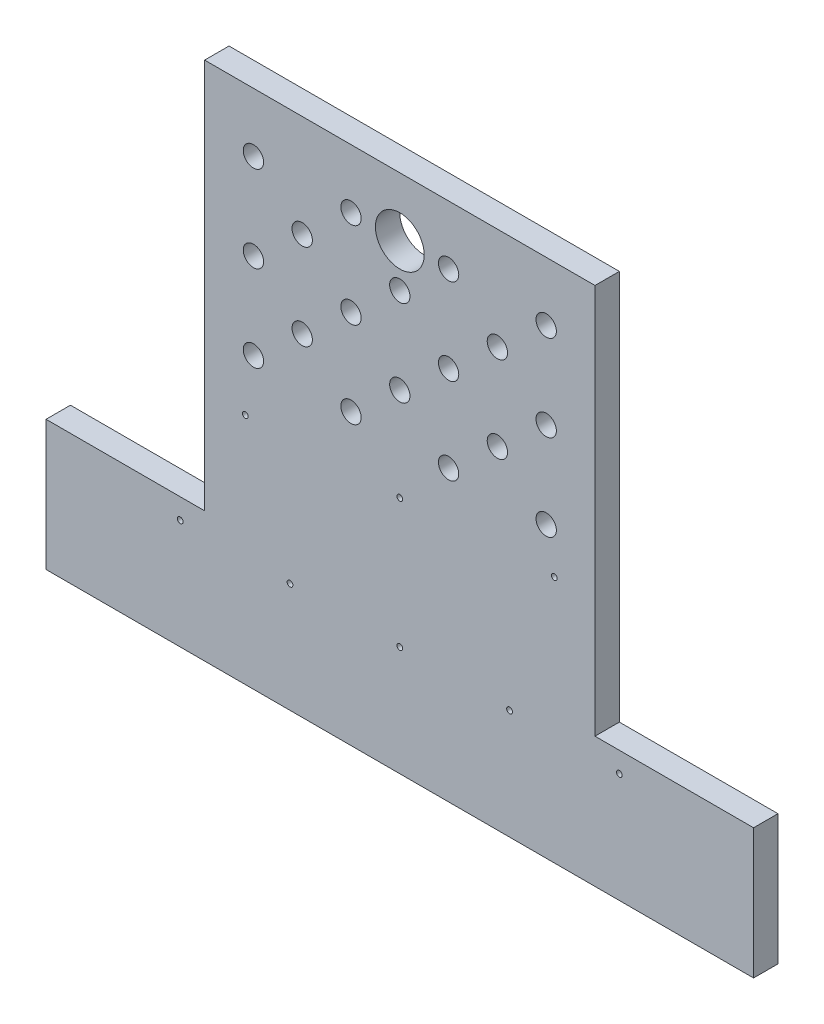
SolidWorks part; units mm, degrees
material "Pine"
ref_plane "Front Plane" through (0, 0, 0) normal (0, 0, 1) x (1, 0, 0)
ref_plane "Top Plane" through (0, 0, 0) normal (0, 1, 0) x (1, 0, 0)
ref_plane "Right Plane" through (0, 0, 0) normal (1, 0, 0) x (0, 0, -1)
sketch "Sketch1" plane through (0, 0, 0) normal (0, 0, 1) x (1, 0, 0)
  line L0 (-152.4, 50.8) -> (-152.4, 355.6)
  line L1 (-276.225, -50.8) -> (276.225, -50.8)
  line L2 (-276.225, -50.8) -> (-276.225, 50.8)
  line L3 (-276.225, 50.8) -> (276.225, 50.8) construction
  line L4 (276.225, -50.8) -> (276.225, 50.8)
  line L5 (-276.225, -50.8) -> (276.225, 50.8) construction
  line L6 (-276.225, 50.8) -> (276.225, -50.8) construction
  line L7 (-152.4, 355.6) -> (152.4, 355.6)
  line L8 (152.4, 355.6) -> (152.4, 50.8)
  line L9 (0, 0) -> (0, 355.6) construction
  line L10 (-152.4, 50.8) -> (-276.225, 50.8)
  line L11 (152.4, 50.8) -> (276.225, 50.8)
  point P0 (0, 0)
  dimension "D1" = 552.45
  dimension "D2" = 101.6
  dimension "D3" = 304.8
  dimension "D4" = 304.8
extrude "Boss-Extrude1" add sketch "Sketch1" along normal blind 19.05
sketch "Sketch2" plane through (0, 0, 19.05) normal (0, 0, 1) x (1, 0, 0)
  line L0 (-76.2, 355.6) -> (-76.2, -50.8) construction
  line L1 (152.4, 355.6) -> (-152.4, 355.6) construction
  line L2 (-276.225, -50.8) -> (276.225, -50.8) construction
  line L3 (0, 355.6) -> (0, -50.8) construction
  line L4 (76.2, 355.6) -> (76.2, -50.8) construction
  line L5 (152.4, 355.6) -> (152.4, -50.8) construction
  line L6 (-152.4, 355.6) -> (-152.4, -50.8) construction
  line L7 (-114.3, 355.6) -> (-114.3, -50.8) construction
  line L8 (-38.1, -50.8) -> (-38.1, 355.6) construction
  line L9 (38.1, 355.6) -> (38.1, -50.8) construction
  line L10 (114.3, -50.8) -> (114.3, 355.6) construction
  line L11 (-114.3, 309.5625) -> (-114.3, 242.2525) construction
  line L12 (-114.3, 242.2525) -> (-114.3, 174.9425) construction
  circle A0 centre (-114.3, 309.5625) radius 7.9375
  circle A1 centre (-38.1, 309.5625) radius 7.9375
  circle A2 centre (38.1, 309.5625) radius 7.9375
  circle A3 centre (114.3, 309.5625) radius 7.9375
  circle A4 centre (-76.2, 275.9075) radius 7.9375
  circle A5 centre (0, 275.9075) radius 7.9375
  circle A6 centre (76.2, 275.9075) radius 7.9375
  circle A8 centre (-114.3, 242.2525) radius 7.9375
  circle A9 centre (-38.1, 242.2525) radius 7.9375
  circle A10 centre (38.1, 242.2525) radius 7.9375
  circle A11 centre (114.3, 242.2525) radius 7.9375
  circle A12 centre (76.2, 208.5975) radius 7.9375
  circle A13 centre (0, 208.5975) radius 7.9375
  circle A14 centre (-76.2, 208.5975) radius 7.9375
  circle A15 centre (-114.3, 174.9425) radius 7.9375
  circle A16 centre (-38.1, 174.9425) radius 7.9375
  circle A17 centre (38.1, 174.9425) radius 7.9375
  circle A18 centre (114.3, 174.9425) radius 7.9375
  point P36 (-76.2, 283.845)
  point P39 (-114.3, 301.625)
  point P42 (-114.3, 317.5)
  point P43 (-114.3, 250.19)
  point P44 (-76.2, 267.97)
  point P61 (-114.3, 182.88)
  point P69 (-76.2, 200.66)
  dimension "D1" = 15.875
  dimension "D2" = 17.78
  dimension "D6" = 17.78
  dimension "D8" = 17.78
  dimension "D3" = 38.1
  dimension "D5" = 2
  dimension "D7" = 2
extrude "Cut-Extrude1" cut sketch "Sketch2" against normal through all
sketch "Sketch5" plane through (0, 0, 0) normal (0, 0, -1) x (-1, 0, 0)
  line L0 (-85.725, 34.925) -> (-171.45, 34.925) construction
  line L2 (-85.725, 34.925) -> (0, 34.925) construction
  line L3 (0, 34.925) -> (85.725, 34.925) construction
  line L4 (85.725, 34.925) -> (171.45, 34.925) construction
  line L5 (171.45, 34.925) -> (257.175, 34.925) construction
  line L6 (257.175, 50.8) -> (257.175, 19.05) construction
  line L7 (-171.45, 34.925) -> (-257.175, 34.925) construction
  line L8 (-257.175, 50.8) -> (-257.175, 19.05) construction
hole_wizard "CSK for #8 Flat Head Machine Screw1" positions "Sketch6" profile "Sketch7" countersink size "#8" standard "ANSI Inch" end condition through all
sketch "Sketch6" plane through (0, 0, 0) normal (0, 0, -1) x (-1, 0, 0)
  point P1 (-171.45, 34.925)
  point P4 (-85.725, 34.925)
  point P7 (0, 34.925)
  point P10 (171.45, 34.925)
  point P13 (85.725, 34.925)
  point P16 (-120.65, 142.5793)
  point P18 (0, 135.7913)
  point P20 (120.65, 131.4668)
sketch "Sketch7" plane through (171.45, 34.925, 0) normal (1, 0, 0) x (0, 1, 0)
  line L0 (0, 0) -> (0, 19.05)
  line L1 (0, 19.05) -> (2.2479, 19.05)
  line L2 (2.2479, 19.05) -> (2.2479, 2.2645)
  line L3 (2.2479, 2.2645) -> (4.2164, 0)
  line L5 (4.2164, 0) -> (0, 0)
  line L6 (-2.2479, 2.2645) -> (-4.2164, 0) construction
  line L11 (0, -6.35) -> (0, 107.95) construction
  dimension "Thru Hole Dia." = 4.4958
  dimension "Thru Hole Depth" = 19.05
  dimension "Near C'Sink Dia." = 8.4328
  dimension "Near C'Sink Angle" = 82
hole_wizard "Hole1" positions "Sketch9" profile "Sketch10" legacy end condition through all
sketch "Sketch9" plane through (0, 0, 19.05) normal (0, 0, 1) x (1, 0, 0)
  line L0 (-38.1, 309.5625) -> (38.1, 309.5625) construction
  point P0 (0, 309.5625)
sketch "Sketch10" plane through (0, 309.5625, 19.05) normal (1, 0, 0) x (0, -1, 0)
  line L0 (0, 0) -> (0, 19.05)
  line L1 (0, 19.05) -> (19.05, 19.05)
  line L2 (19.05, 19.05) -> (19.05, 0)
  line L3 (19.05, 0) -> (0, 0)
  line L4 (0, 110) -> (0, -10) construction
  dimension "Diameter" = 38.1
  dimension "Depth" = 19.05
sketch "Sketch13" plane through (0, 0, 0) normal (0, 0, -1) x (-1, 0, 0)
  line B0 (-276.225, -50.8) -> (276.225, -50.8)
  line B1 (30.2754, 281.3107) -> (30.2765, 290.0355)
  line B2 (30.2746, 258.2859) -> (30.2746, 267.0107)
  arc B3 (19.7008, 287.3363) -> (22.3391, 289.9991) centre (19.7009, 289.9746) ccw
  arc B4 (22.3372, 258.3232) -> (19.6992, 260.9863) centre (19.6991, 258.348) ccw
  arc B5 (-26.9928, 286.1302) -> (-24.5316, 286.489) centre (-26.3058, 290.0391) ccw
  arc B6 (-22.3372, 290.0018) -> (-19.6992, 287.3387) centre (-19.6991, 289.977) ccw
  circle B7 centre (26.3077, 290.0359) radius 1.4732
  circle B8 centre (26.3058, 258.2859) radius 1.4732
  circle B9 centre (-26.3077, 258.2891) radius 1.4732
  circle B10 centre (-26.3058, 290.0391) radius 1.4732
sketch_block_instance "Dropper Mounting Holes-1"
sketch_block "Dropper Mounting Holes"
hole_wizard "5/64 (0.07813) Diameter Hole1" positions "Sketch14" profile "Sketch15" hole size "5/64" standard "ANSI Inch"
sketch "Sketch14" plane through (0, 0, 0) normal (0, 0, -1) x (-1, 0, 0)
  point P0 (-26.3058, 290.0391)
  point P3 (-26.3077, 258.2891)
  point P6 (26.3058, 258.2859)
  point P14 (26.3077, 290.0359)
sketch "Sketch15" plane through (26.3058, 290.0391, 0) normal (1, 0, 0) x (0, 1, 0)
  line L0 (0, 0) -> (0, 11.7214)
  line L1 (0, 11.7214) -> (0.9923, 11.1252)
  line L2 (0.9923, 11.1252) -> (0.9923, 0)
  line L5 (0.9923, 0) -> (0, 0)
  line L10 (0, 11.7214) -> (-0.9923, 11.1252) construction
  line L11 (0, -6.35) -> (0, 107.95) construction
  dimension "Hole Dia." = 1.9845
  dimension "Hole Depth" = 11.1252
  dimension "Drill Angle" = 118
equation "\"2.5325‬\"=6.68551"
equation "\"Pachinko\"= .7"
equation "\"D2@Sketch2\"=\"Pachinko\""
equation "\"D6@Sketch2\"=\"Pachinko\""
equation "\"D8@Sketch2\"=\"Pachinko\""
